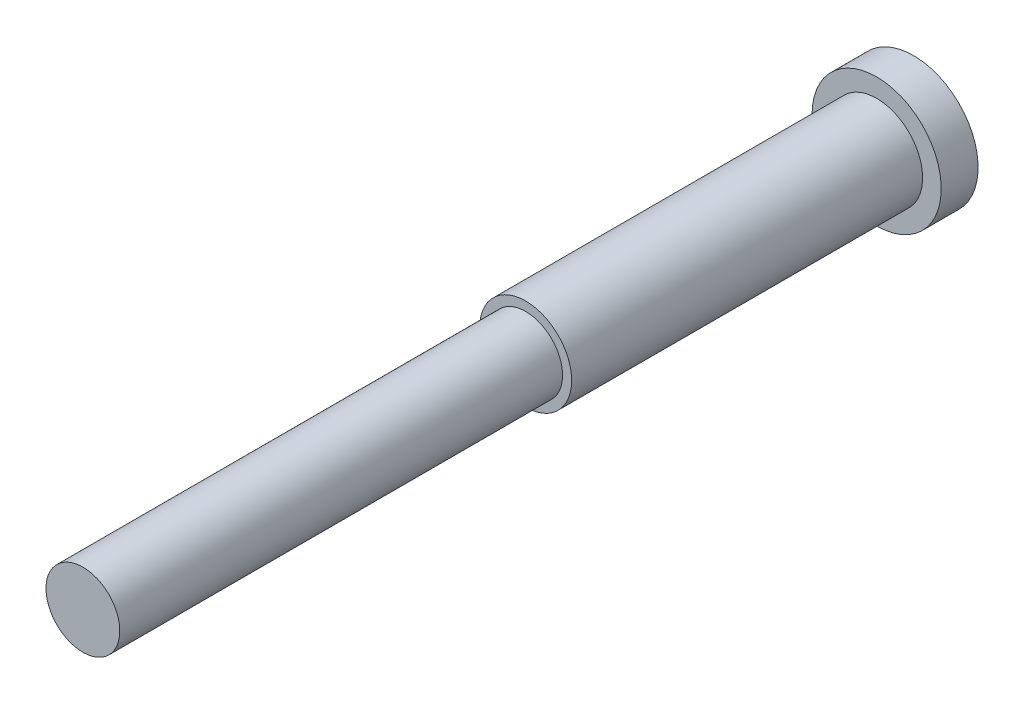
SolidWorks part; units mm, degrees
material "PW20:29:Sc:0:"
ref_plane "Front" through (0, 0, 0) normal (0, 0, 1) x (1, 0, 0)
ref_plane "Top" through (0, 0, 0) normal (0, 1, 0) x (1, 0, 0)
ref_plane "Right" through (0, 0, 0) normal (1, 0, 0) x (0, 0, -1)
sketch "Sketch1" plane through (0, 0, 0) normal (0, 0, 1) x (1, 0, 0)
  circle A0 centre (0, 0) radius 7.9121
  dimension "D1" = 15.8242
extrude "Base-Extrude" add sketch "Sketch1" along normal blind 60.4012
sketch "Sketch2" plane through (0, 0, 60.4012) normal (0, 0, 1) x (1, 0, 0)
  circle A0 centre (0, 0) radius 6.35
  dimension "D1" = 12.7
extrude "Boss-Extrude1" add sketch "Sketch2" along normal blind 76.2
sketch "Sketch3" plane through (0, 0, 0) normal (0, 0, -1) x (-1, 0, 0)
  circle A0 centre (0, 0) radius 11.1125
  dimension "D1" = 22.225
extrude "Boss-Extrude2" add sketch "Sketch3" along normal blind 6.35
ref_plane "Place" through (0, 0, 53.34) normal (0, 0, 1) x (1, 0, 0)
